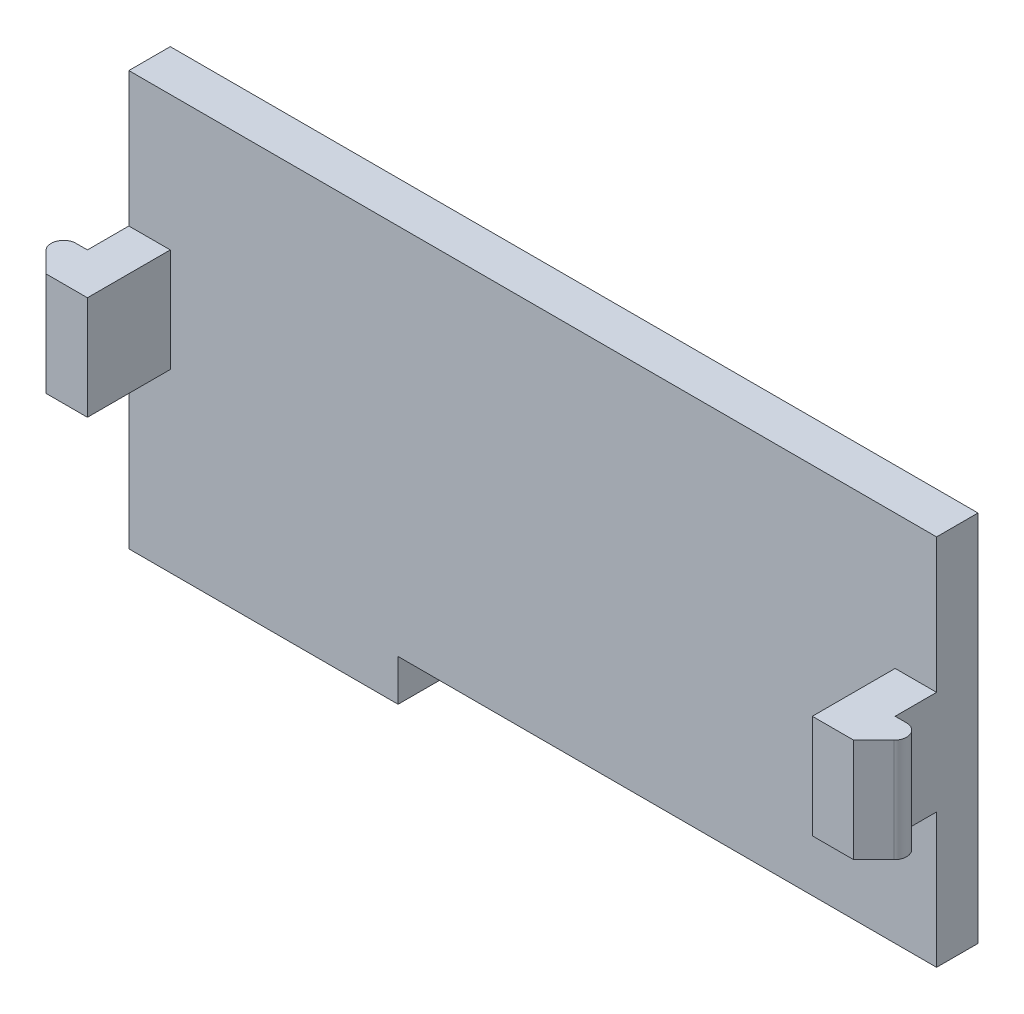
SolidWorks part; units mm, degrees
ref_plane "Front Plane" through (0, 0, 0) normal (0, 0, 1) x (1, 0, 0)
ref_plane "Top Plane" through (0, 0, 0) normal (0, 1, 0) x (1, 0, 0)
ref_plane "Right Plane" through (0, 0, 0) normal (1, 0, 0) x (0, 0, -1)
sketch "Sketch1" plane through (0, 0, 0) normal (0, 0, 1) x (1, 0, 0)
  line L1 (0, 0) -> (40, 0)
  line L2 (0, 0) -> (0, -18)
  line L3 (0, -18) -> (40, -18)
  line L4 (40, 0) -> (40, -18)
  dimension "D1" = 40
  dimension "D2" = 18
extrude "Boss-Extrude1" add sketch "Sketch1" along normal blind 2
sketch "Sketch2" plane through (0, 0, 2) normal (0, 0, 1) x (1, 0, 0)
  line L1 (1, -6.5) -> (3, -6.5)
  line L2 (1, -6.5) -> (1, -11.5)
  line L3 (1, -11.5) -> (3, -11.5)
  line L4 (3, -6.5) -> (3, -11.5)
  line L5 (40, -18) -> (40, 0) construction
  line L6 (40, -6.5) -> (38, -6.5)
  line L7 (40, -6.5) -> (40, -11.5)
  line L8 (40, -11.5) -> (38, -11.5)
  line L9 (38, -6.5) -> (38, -11.5)
  line L10 (0, -18) -> (40, -18) construction
  point P14 (0, 0)
  point P15 (0, 0)
  dimension "D1" = 5
  dimension "D2" = 2
  dimension "D3" = 5
  dimension "D4" = 2
  dimension "D5" = 6.5
  dimension "D6" = 6.5
  dimension "D7" = 37
extrude "Boss-Extrude2" add sketch "Sketch2" along normal blind 2
sketch "Sketch3" plane through (0, -11.5, 0) normal (0, -1, 0) x (1, 0, 0)
  line L0 (0, 4) -> (-1, 4)
  line L1 (-1, 4) -> (1, 6)
  line L2 (1, 6) -> (3, 6)
  line L3 (3, 6) -> (3, 4)
  line L4 (38, 4) -> (38, 6)
  line L5 (38, 6) -> (40, 6)
  line L6 (40, 6) -> (42, 4)
  line L7 (42, 4) -> (40, 4)
  line L8 (40, 4) -> (38, 4)
  line L9 (3, 4) -> (0, 4)
  point P10 (3, 6)
  point P15 (-2, 4)
  point P16 (0, 0)
  point P18 (-0.8129, 2.0999)
  point P19 (-2.6795, 4.659)
  dimension "D1" = 2
  dimension "D2" = 2
  dimension "D3" = 2
  dimension "D4" = 2
  dimension "D5" = 2
  dimension "D6" = 2
extrude "Boss-Extrude3" add sketch "Sketch3" against normal up to surface (5 mm away) up to face at (39, -6.5, 3)
fillet "Fillet1" radius 0.6 2 edges at (42, -9, 4) (-1, -9, 4)
sketch "Sketch4" plane through (0, 0, 0) normal (0, 0, -1) x (-1, 0, 0)
  line L0 (0, -18) -> (0, -20)
  line L1 (0, -20) -> (-13, -20)
  line L2 (-13, -20) -> (-13, -18)
  line L3 (0, -18) -> (-40, -18) construction
  line L4 (-13, -18) -> (0, -18)
  dimension "D1" = 2
  dimension "D2" = 13
extrude "Boss-Extrude4" add sketch "Sketch4" against normal up to surface (2 mm away) up to face at (2, -9, 2)
sketch "Sketch5" plane through (0, 0, 2) normal (0, 0, 1) x (1, 0, 0)
  line L0 (13, -20) -> (0, -20) construction
  line L1 (0, 0) -> (1, 0)
  line L2 (0, 0) -> (0, -20)
  line L3 (0, -20) -> (1, -20)
  line L4 (1, 0) -> (1, -20)
  dimension "D1" = 1
extrude "Cut-Extrude1" cut sketch "Sketch5" against normal blind 10
sketch "Sketch6" plane through (0, 0, 2) normal (0, 0, 1) x (1, 0, 0)
  line L0 (13, -18) -> (40, -18) construction
  line L1 (13, -20) -> (14, -20)
  line L2 (13, -20) -> (13, -18)
  line L3 (13, -18) -> (14, -18)
  line L4 (14, -20) -> (14, -18)
  dimension "D1" = 1
extrude "Boss-Extrude5" add sketch "Sketch6" against normal up to surface (2 mm away) up to face at (18, -12.6667, 0)
